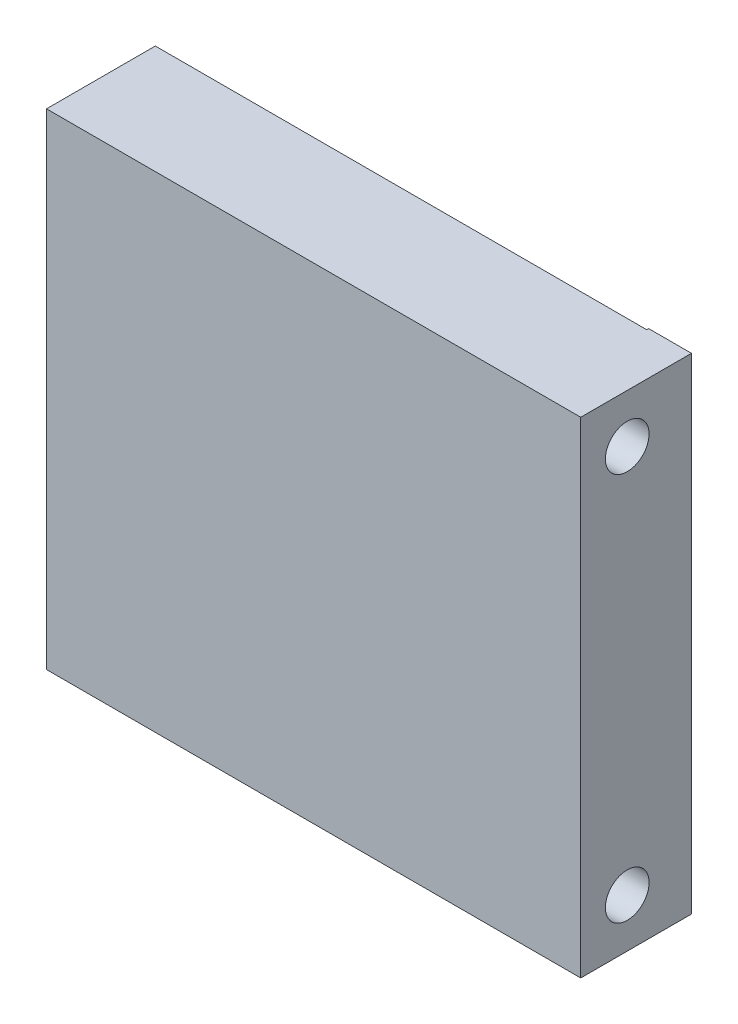
SolidWorks part; units mm, degrees
ref_plane "Front Plane" through (0, 0, 0) normal (1, 0, 0) x (0, 1, 0)
ref_plane "Top Plane" through (0, 0, 0) normal (0, 0, 1) x (0, 1, 0)
ref_plane "Right Plane" through (0, 0, 0) normal (0, 1, 0) x (-1, 0, 0)
sketch "Sketch1" plane through (0, 0, 0) normal (0, 0, 1) x (0, 1, 0)
  line L1 (-25, 25.3) -> (19, 25.3)
  line L2 (-25, 25.3) -> (-25, -25.3)
  line L3 (-25, -25.3) -> (25, -25.3)
  line L4 (25, 25.3) -> (25, -25.3)
  line L5 (-25, 25.3) -> (25, -25.3) construction
  line L6 (-25, -25.3) -> (25, 25.3) construction
  line L9 (19, 25.3) -> (25, 25.3)
  point P0 (0, 0)
  dimension "D1" = 50
  dimension "D2" = 50.6
extrude "Boss-Extrude1" add sketch "Sketch1" along normal blind 1
sketch "Sketch2" plane through (25.3, 0, 0) normal (1, 0, 0) x (0, 1, 0)
  line L1 (25, 1) -> (-25, 1)
  line L2 (25, 1) -> (25, -10.4)
  line L3 (25, -10.4) -> (-25, -10.4)
  line L4 (-25, 1) -> (-25, -10.4)
  dimension "D1" = 11.4
extrude "Boss-Extrude2" add sketch "Sketch2" along normal blind 4.4
sketch "Sketch3" plane through (29.7, 0, 0) normal (1, 0, 0) x (0, 1, 0)
  line L0 (-20, -3.7871) -> (20, -3.7871) construction
  line L1 (-25, 1) -> (-25, -10.4) construction
  circle A0 centre (-20, -3.7871) radius 2.25
  circle A1 centre (20, -3.7871) radius 2.25
  dimension "D1" = 4.5
  dimension "D2" = 4.5
  dimension "D3" = 40
  dimension "D4" = 5
extrude "Cut-Extrude1" cut sketch "Sketch3" against normal blind 4.4
sketch "Sketch4" plane through (0, 0, 0) normal (0, 0, -1) x (1, 0, 0)
  line L0 (-25.3, -19.5) -> (-25.3, -25)
  line L1 (-25.3, 19.5) -> (25.3, 19.5)
  line L3 (-25.3, -19.5) -> (25.3, -19.5)
  line L7 (-25.3, 25) -> (25.3, 25)
  line L8 (-25.3, 25) -> (-25.3, 19.5)
  line L9 (-25.3, -25) -> (25.3, -25)
  line L10 (25.3, 25) -> (25.3, 19.5)
  line L11 (-25.3, 25) -> (-19.734, 19.5) construction
  line L12 (-25.3, -25) -> (-19.734, -19.5) construction
  line L13 (19.734, 19.5) -> (25.3, 25) construction
  line L14 (19.734, -19.5) -> (25.3, -25) construction
  line L15 (25.3, -19.5) -> (25.3, -25)
  point P0 (0, 0)
  point P6 (0, 0)
  dimension "D1" = 50.6
  dimension "D2" = 39
  dimension "D3" = 5.5
  dimension "D4" = 5.5
extrude "Boss-Extrude3" add sketch "Sketch4" along normal blind 6.4
sketch "Sketch5" plane through (0, 0, -6.4) normal (0, 0, -1) x (1, 0, 0)
  line L0 (-25.3, 20.5) -> (-25.3, 25)
  line L5 (25.3, -25) -> (-25.3, -25)
  line L6 (25.3, -20.5) -> (-25.3, -20.5)
  line L13 (25.3, 20.5) -> (-25.3, 20.5)
  line L18 (25.3, -25) -> (25.3, -20.5)
  line L19 (25.3, 25) -> (-25.3, 25)
  line L20 (-25.3, -25) -> (-25.3, -20.5)
  line L21 (25.3, -25) -> (20.746, -20.5) construction
  line L22 (25.3, 25) -> (20.746, 20.5) construction
  line L23 (-20.746, -20.5) -> (-25.3, -25) construction
  line L24 (-20.746, 20.5) -> (-25.3, 25) construction
  line L25 (25.3, 20.5) -> (25.3, 25)
  point P0 (0, 0)
  point P5 (0, 0)
  dimension "D1" = 41
  dimension "D2" = 50.6
extrude "Boss-Extrude4" add sketch "Sketch5" along normal blind 1.8
sketch "Sketch6" plane through (0, 0, -8.2) normal (0, 0, -1) x (1, 0, 0)
  line L0 (-25.3, -19.5) -> (-25.3, -25)
  line L5 (19.734, -19.5) -> (25.3, -25) construction
  line L23 (25.3, 19.5) -> (-25.3, 19.5)
  line L37 (25.3, -19.5) -> (-25.3, -19.5)
  line L41 (-25.3, 25) -> (25.3, 25)
  line L42 (-25.3, 25) -> (-25.3, 19.5)
  line L43 (-25.3, -25) -> (25.3, -25)
  line L44 (25.3, 25) -> (25.3, 19.5)
  line L46 (-25.3, -25) -> (-19.734, -19.5) construction
  line L47 (25.3, -19.5) -> (25.3, -25)
  point P0 (0, 0)
  point P6 (0, 0)
  dimension "D1" = 50.6
  dimension "D2" = 39
  dimension "D3" = 50.6
  dimension "D4" = 50
extrude "Boss-Extrude5" add sketch "Sketch6" along normal blind 2
